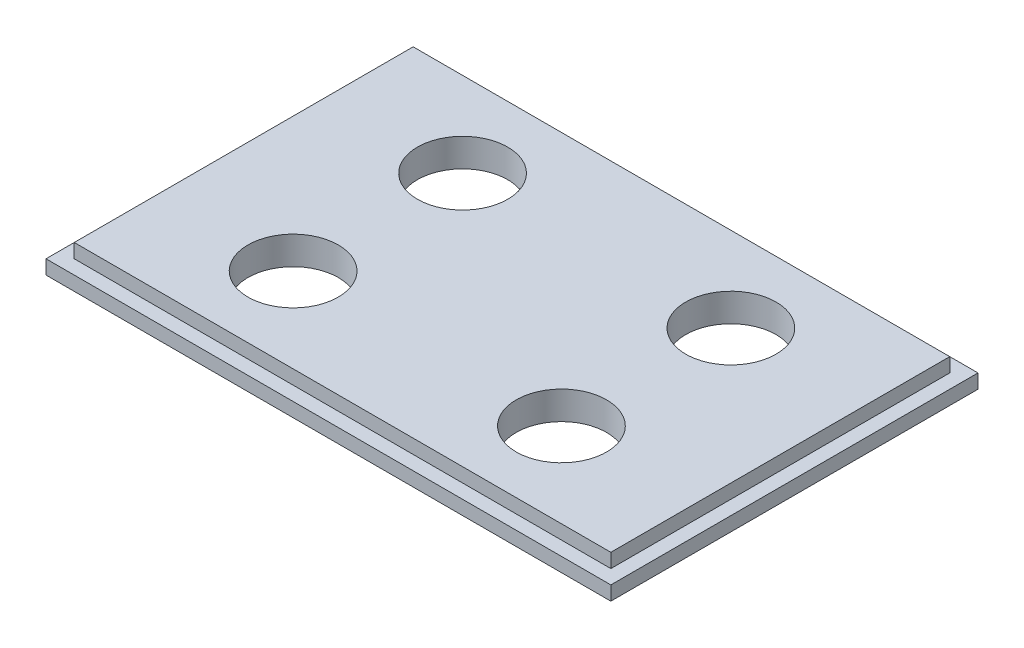
SolidWorks part; units mm, degrees
ref_plane "Front Plane" through (0, 0, 0) normal (0, 0, 1) x (1, 0, 0)
ref_plane "Top Plane" through (0, 0, 0) normal (0, 1, 0) x (1, 0, 0)
ref_plane "Right Plane" through (0, 0, 0) normal (1, 0, 0) x (0, 0, -1)
sketch "Sketch2" plane through (0, 0, 0) normal (0, 1, 0) x (1, 0, 0)
  line L1 (-127, -82.55) -> (127, -82.55)
  line L2 (-127, -82.55) -> (-127, 82.55)
  line L3 (-127, 82.55) -> (127, 82.55)
  line L4 (127, -82.55) -> (127, 82.55)
  line L5 (-127, -82.55) -> (127, 82.55) construction
  line L6 (-127, 82.55) -> (127, -82.55) construction
  point P0 (0, 0)
  dimension "D1" = 254
  dimension "D2" = 165.1
extrude "Boss-Extrude1" add sketch "Sketch2" along normal blind 6.35
sketch "Sketch3" plane through (0, 6.35, 0) normal (0, 1, 0) x (1, 0, 0)
  line L1 (-120.65, -76.2) -> (120.65, -76.2)
  line L2 (-120.65, -76.2) -> (-120.65, 76.2)
  line L3 (-120.65, 76.2) -> (120.65, 76.2)
  line L4 (120.65, -76.2) -> (120.65, 76.2)
  line L5 (-120.65, -76.2) -> (120.65, 76.2) construction
  line L6 (-120.65, 76.2) -> (120.65, -76.2) construction
  point P0 (0, 0)
  dimension "D1" = 241.3
  dimension "D2" = 152.4
extrude "Boss-Extrude2" add sketch "Sketch3" along normal blind 6.35
sketch "Sketch4" plane through (0, 12.7, 0) normal (0, 1, 0) x (1, 0, 0)
  line L0 (120.65, 0) -> (-120.65, 0) construction
  line L1 (120.65, -76.2) -> (120.65, 76.2) construction
  line L2 (-120.65, 76.2) -> (-120.65, -76.2) construction
  line L3 (0, 76.2) -> (0, -76.2) construction
  line L4 (120.65, 76.2) -> (-120.65, 76.2) construction
  line L5 (-120.65, -76.2) -> (120.65, -76.2) construction
  line L6 (0, 0) -> (-120.65, 76.2) construction
  circle A1 centre (-60.325, 38.1) radius 20.32
  circle A2 centre (60.325, 38.1) radius 20.32
  circle A3 centre (60.325, -38.1) radius 20.32
  circle A4 centre (-60.325, -38.1) radius 20.32
  dimension "D1" = 40.64
extrude "Cut-Extrude2" cut sketch "Sketch4" against normal through all
